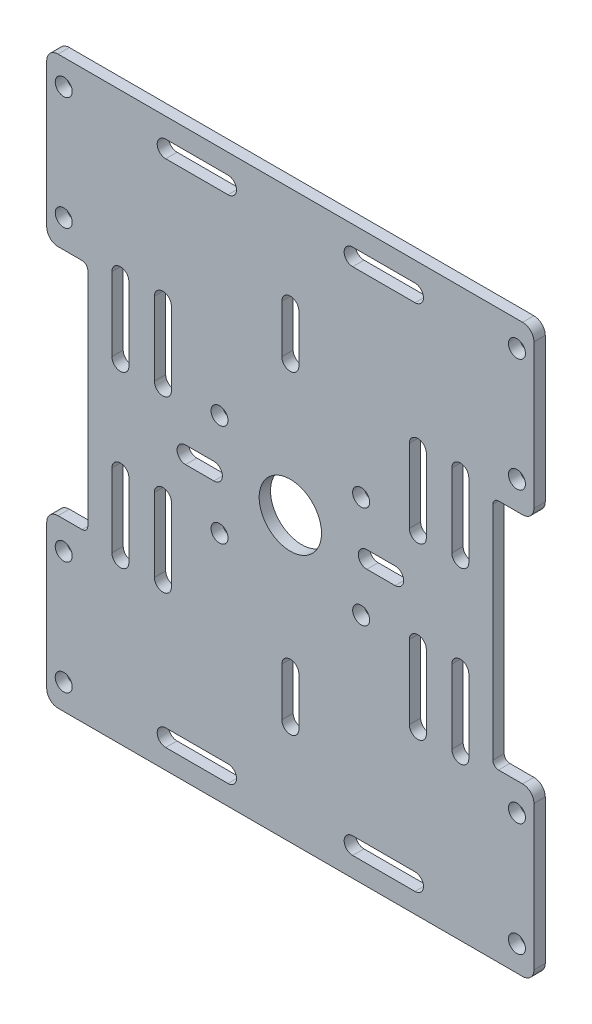
SolidWorks part; units mm, degrees
ref_plane "前基準面" through (0, 0, 0) normal (0, 0, 1) x (1, 0, 0)
ref_plane "上基準面" through (0, 0, 0) normal (0, 1, 0) x (1, 0, 0)
ref_plane "右基準面" through (0, 0, 0) normal (1, 0, 0) x (0, 0, -1)
sketch "草圖1" plane through (0, 0, 0) normal (0, 0, 1) x (1, 0, 0)
  line L0 (-13.5, 0) -> (-18.5, 0) construction
  line L3 (13.5, 0) -> (18.5, 0) construction
  line L4 (13.5, 1.5) -> (18.5, 1.5)
  line L5 (13.5, -1.5) -> (18.5, -1.5)
  line L6 (22.5, -8.5) -> (22.5, -21.5) construction
  line L7 (24, -8.5) -> (24, -21.5)
  line L8 (21, -8.5) -> (21, -21.5)
  line L9 (30, -8.5) -> (30, -21.5) construction
  line L12 (-167.459, 0) -> (250.2577, 0) construction
  line L13 (0, 741.9689) -> (0, -704.7384) construction
  line L14 (31.5, -8.5) -> (31.5, -21.5)
  line L15 (28.5, -8.5) -> (28.5, -21.5)
  line L16 (30, 8.5) -> (30, 21.5) construction
  line L17 (31.5, 8.5) -> (31.5, 21.5)
  line L18 (28.5, 8.5) -> (28.5, 21.5)
  line L19 (22.5, 8.5) -> (22.5, 21.5) construction
  line L20 (24, 8.5) -> (24, 21.5)
  line L21 (21, 8.5) -> (21, 21.5)
  line L22 (-22.5, 8.5) -> (-22.5, 21.5) construction
  line L23 (-24, 8.5) -> (-24, 21.5)
  line L24 (-21, 8.5) -> (-21, 21.5)
  line L25 (-30, 8.5) -> (-30, 21.5) construction
  line L26 (-31.5, 8.5) -> (-31.5, 21.5)
  line L27 (-28.5, 8.5) -> (-28.5, 21.5)
  line L28 (-30, -8.5) -> (-30, -21.5) construction
  line L29 (-31.5, -8.5) -> (-31.5, -21.5)
  line L30 (-28.5, -8.5) -> (-28.5, -21.5)
  line L31 (-22.5, -8.5) -> (-22.5, -21.5) construction
  line L32 (-24, -8.5) -> (-24, -21.5)
  line L33 (-21, -8.5) -> (-21, -21.5)
  line L34 (-22, -45) -> (-11, -45) construction
  line L35 (-22, -43.5) -> (-11, -43.5)
  line L36 (-22, -46.5) -> (-11, -46.5)
  line L37 (22, -45) -> (11, -45) construction
  line L38 (22, -43.5) -> (11, -43.5)
  line L39 (22, -46.5) -> (11, -46.5)
  line L40 (22, 45) -> (11, 45) construction
  line L41 (22, 43.5) -> (11, 43.5)
  line L42 (22, 46.5) -> (11, 46.5)
  line L43 (-22, 45) -> (-11, 45) construction
  line L44 (-22, 43.5) -> (-11, 43.5)
  line L45 (-22, 46.5) -> (-11, 46.5)
  line L46 (-35.75, -20.5625) -> (-43, -20.5625)
  line L47 (-25.75, -50) -> (25.75, -50)
  line L48 (-35.75, -20.5625) -> (-35.75, 20.5625)
  line L49 (-25.75, 50) -> (25.75, 50)
  line L50 (35.75, -20.5625) -> (35.75, 20.5625)
  line L51 (-35.75, -50) -> (35.75, 50) construction
  line L52 (-35.75, 50) -> (35.75, -50) construction
  line L53 (-13.5, 1.5) -> (-18.5, 1.5)
  line L54 (-13.5, -1.5) -> (-18.5, -1.5)
  line L55 (0, -23.5) -> (0, -32) construction
  line L56 (1.5, -23.5) -> (1.5, -32)
  line L57 (-1.5, -23.5) -> (-1.5, -32)
  line L58 (0, 23.5) -> (0, 32) construction
  line L59 (1.5, 23.5) -> (1.5, 32)
  line L60 (-1.5, 23.5) -> (-1.5, 32)
  line L61 (-43, -20.5625) -> (-43, -50)
  line L62 (-43, -50) -> (-25.75, -50)
  line L63 (43, -50) -> (25.75, -50)
  line L64 (43, -20.5625) -> (43, -50)
  line L65 (35.75, -20.5625) -> (43, -20.5625)
  line L66 (35.75, 20.5625) -> (43, 20.5625)
  line L67 (43, 20.5625) -> (43, 50)
  line L68 (43, 50) -> (25.75, 50)
  line L69 (-43, 50) -> (-25.75, 50)
  line L70 (-43, 20.5625) -> (-43, 50)
  line L71 (-35.75, 20.5625) -> (-43, 20.5625)
  circle A0 centre (0, 0) radius 5.5
  circle A4 centre (12.5, -9) radius 1.5
  arc A7 (13.5, 1.5) -> (13.5, -1.5) centre (13.5, 0) ccw
  arc A8 (18.5, -1.5) -> (18.5, 1.5) centre (18.5, 0) ccw
  arc A9 (24, -8.5) -> (21, -8.5) centre (22.5, -8.5) ccw
  arc A10 (21, -21.5) -> (24, -21.5) centre (22.5, -21.5) ccw
  arc A13 (31.5, -8.5) -> (28.5, -8.5) centre (30, -8.5) ccw
  arc A14 (28.5, -21.5) -> (31.5, -21.5) centre (30, -21.5) ccw
  arc A15 (31.5, 8.5) -> (28.5, 8.5) centre (30, 8.5) cw
  arc A16 (28.5, 21.5) -> (31.5, 21.5) centre (30, 21.5) cw
  arc A17 (24, 8.5) -> (21, 8.5) centre (22.5, 8.5) cw
  arc A18 (21, 21.5) -> (24, 21.5) centre (22.5, 21.5) cw
  arc A19 (-24, 8.5) -> (-21, 8.5) centre (-22.5, 8.5) ccw
  arc A20 (-21, 21.5) -> (-24, 21.5) centre (-22.5, 21.5) ccw
  arc A21 (-31.5, 8.5) -> (-28.5, 8.5) centre (-30, 8.5) ccw
  arc A22 (-28.5, 21.5) -> (-31.5, 21.5) centre (-30, 21.5) ccw
  arc A23 (-31.5, -8.5) -> (-28.5, -8.5) centre (-30, -8.5) cw
  arc A24 (-28.5, -21.5) -> (-31.5, -21.5) centre (-30, -21.5) cw
  arc A25 (-24, -8.5) -> (-21, -8.5) centre (-22.5, -8.5) cw
  arc A26 (-21, -21.5) -> (-24, -21.5) centre (-22.5, -21.5) cw
  arc A27 (-22, -43.5) -> (-22, -46.5) centre (-22, -45) ccw
  arc A28 (-11, -46.5) -> (-11, -43.5) centre (-11, -45) ccw
  arc A29 (22, -43.5) -> (22, -46.5) centre (22, -45) cw
  arc A30 (11, -46.5) -> (11, -43.5) centre (11, -45) cw
  arc A31 (22, 43.5) -> (22, 46.5) centre (22, 45) ccw
  arc A32 (11, 46.5) -> (11, 43.5) centre (11, 45) ccw
  arc A33 (-22, 43.5) -> (-22, 46.5) centre (-22, 45) cw
  arc A34 (-11, 46.5) -> (-11, 43.5) centre (-11, 45) cw
  arc A39 (-13.5, 1.5) -> (-13.5, -1.5) centre (-13.5, 0) cw
  arc A40 (-18.5, -1.5) -> (-18.5, 1.5) centre (-18.5, 0) cw
  circle A41 centre (-12.5, -9) radius 1.5
  circle A42 centre (12.5, 9) radius 1.5
  circle A43 centre (-12.5, 9) radius 1.5
  arc A44 (1.5, -23.5) -> (-1.5, -23.5) centre (0, -23.5) ccw
  arc A45 (-1.5, -32) -> (1.5, -32) centre (0, -32) ccw
  arc A46 (1.5, 23.5) -> (-1.5, 23.5) centre (0, 23.5) cw
  arc A47 (-1.5, 32) -> (1.5, 32) centre (0, 32) cw
  circle A48 centre (-40, -25.5) radius 1.5
  circle A49 centre (40, -25.5) radius 1.5
  circle A50 centre (40, 25.5) radius 1.5
  circle A51 centre (-40, 25.5) radius 1.5
  circle A52 centre (-40, -45.5) radius 1.5
  circle A53 centre (-40, 45.5) radius 1.5
  circle A54 centre (40, 45.5) radius 1.5
  circle A55 centre (40, -45.5) radius 1.5
  point P5 (0, -27.75)
  point P8 (-16, 0)
  point P18 (16, 0)
  point P25 (22.5, -15)
  point P34 (30, -15)
  point P45 (30, 15)
  point P52 (22.5, 15)
  point P59 (-22.5, 15)
  point P66 (-30, 15)
  point P73 (-30, -15)
  point P80 (-22.5, -15)
  point P87 (-16.5, -45)
  point P94 (16.5, -45)
  point P101 (16.5, 45)
  point P108 (-16.5, 45)
  point P140 (0, 27.75)
  dimension "D2" = 11
  dimension "D3" = 3
  dimension "D4" = 5
  dimension "D6" = 1.5
  dimension "D9" = 23.5
  dimension "D10" = 1.5
  dimension "D11" = 1.5
  dimension "D12" = 1.5
  dimension "D13" = 8.5
  dimension "D20" = 8.5
  dimension "D24" = 1.5
  dimension "D21" = 45
  dimension "D5" = 2.5
  dimension "D25" = 25.5
  dimension "D27" = 3
  dimension "D28" = 45.5
  dimension "D29" = 3
  dimension "D7" = 12.5
  dimension "D8" = 9
  dimension "D14" = 60
  dimension "D15" = 7.5
  dimension "D16" = 71.5
  dimension "D17" = 100
  dimension "D18" = 13
  dimension "D19" = 13
  dimension "D22" = 22
  dimension "D23" = 11
  dimension "D26" = 40
  dimension "D30" = 43
extrude "填料-伸長1" add sketch "草圖1" along normal blind 2
fillet "圓角1" radius 1 4 edges at (35.75, -20.5625, 1) (35.75, 20.5625, 1) (-35.75, 20.5625, 1) (-35.75, -20.5625, 1)
fillet "圓角2" radius 2 8 edges at (43, 20.5625, 1) (43, 50, 1) (-43, 50, 1) (-43, 20.5625, 1) (-43, -20.5625, 1) (-43, -50, 1) (43, -50, 1) (43, -20.5625, 1)
